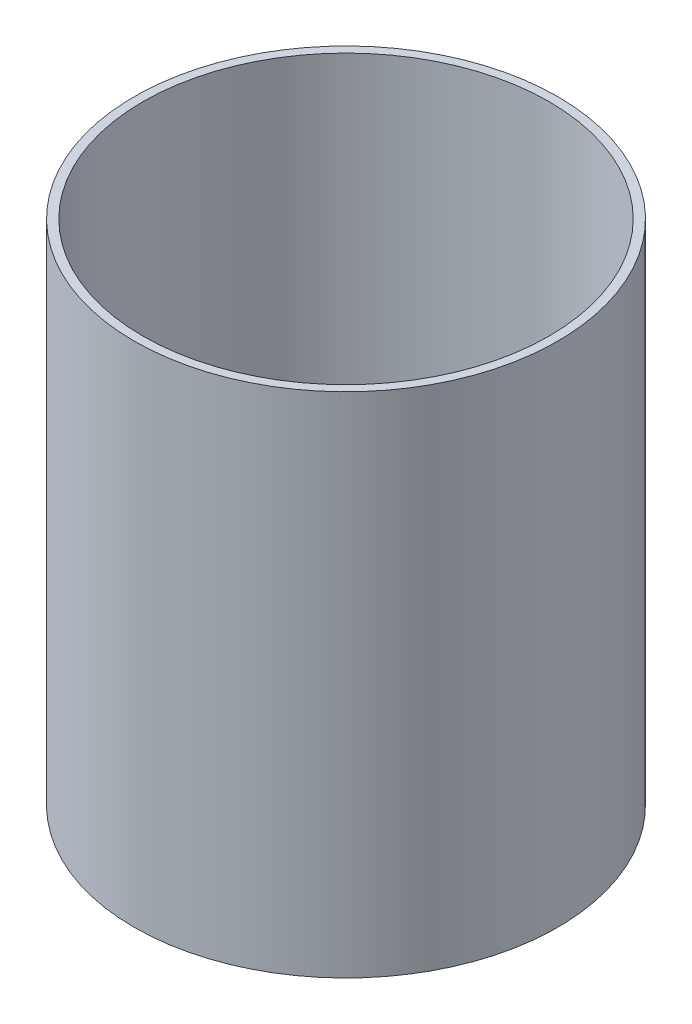
SolidWorks part; units mm, degrees
material "6061 Alloy"
ref_plane "Front Plane" through (0, 0, 0) normal (0, 0, 1) x (1, 0, 0)
ref_plane "Top Plane" through (0, 0, 0) normal (0, 1, 0) x (1, 0, 0)
ref_plane "Right Plane" through (0, 0, 0) normal (1, 0, 0) x (0, 0, -1)
sketch "Sketch1" plane through (0, 0, 0) normal (0, 1, 0) x (1, 0, 0)
  circle A0 centre (-29.3916, 2.6114) radius 24.401
  circle A1 centre (-29.3916, 2.6114) radius 23.401
  dimension "D1" = 1
extrude "Boss-Extrude1" add sketch "Sketch1" along normal blind 58.5
